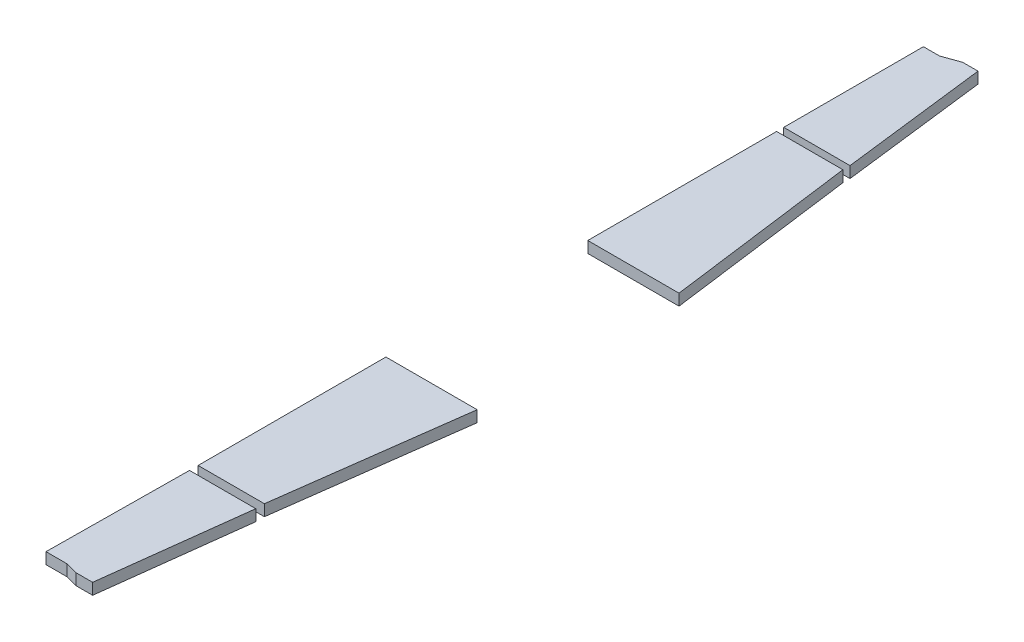
SolidWorks part; units mm, degrees
ref_plane "Front Plane" through (0, 0, 0) normal (0, 0, 1) x (1, 0, 0)
ref_plane "Top Plane" through (0, 0, 0) normal (0, 1, 0) x (1, 0, 0)
ref_plane "Right Plane" through (0, 0, 0) normal (1, 0, 0) x (0, 0, -1)
sketch "Sketch1" plane through (0, 0, 0) normal (0, 1, 0) x (1, 0, 0)
  line L0 (0, 0) -> (1188.6667, 0) construction
  line L1 (1886.6416, -10754.9704) -> (4446.1038, -10754.9704)
  line L2 (4446.1038, -10754.9704) -> (3757.6552, -6813.8602)
  line L3 (3757.6552, -6813.8602) -> (3166.3727, -6813.8602)
  line L4 (3166.3727, -6813.8602) -> (2506.2895, -6979.2389)
  line L5 (2506.2895, -6979.2389) -> (1886.6416, -6979.2389)
  line L6 (1886.6416, -6979.2389) -> (1886.6416, -10754.9704)
  line L7 (1886.6416, -10947.5155) -> (4446.1038, -10947.5155)
  line L8 (1886.6416, -10947.5155) -> (1886.6416, -16051.7647)
  line L9 (1886.6416, -16051.7647) -> (5410.4156, -16051.7647)
  line L10 (5410.4156, -16051.7647) -> (4446.1038, -10947.5155)
  line L11 (1886.6416, -21507.5385) -> (1886.6416, -26583.6069)
  line L12 (1886.6416, -21507.5385) -> (5410.4156, -21507.5385)
  line L13 (5410.4156, -21507.5385) -> (4446.1038, -26583.6069)
  line L14 (4446.1038, -26583.6069) -> (2301.3562, -26583.6069)
  line L15 (2301.3562, -26583.6069) -> (1886.6416, -26583.6069)
  line L16 (1886.6416, -26816.2701) -> (1832.6361, -30657.2626)
  line L17 (1832.6361, -30657.2626) -> (2648.847, -30657.2626)
  line L18 (2648.847, -30657.2626) -> (3108.5383, -30744.5911)
  line L19 (3108.5383, -30744.5911) -> (3757.6552, -30744.5911)
  line L20 (3757.6552, -30744.5911) -> (4446.1038, -26816.2701)
  line L21 (4446.1038, -26816.2701) -> (1886.6416, -26816.2701)
extrude "Boss-Extrude1" add sketch "Sketch1" along normal blind 304.8
sketch "Sketch4" plane through (0, 0, 30744.5911) normal (0, 0, 1) x (1, 0, 0)
  line L12 (1832.6361, 304.8) -> (1832.6361, 0) construction
  line L15 (1832.6361, 304.8) -> (2648.847, 304.8) construction
  circle A0 centre (1959.6361, 152.4) radius 76.2
  dimension "D2" = 152.4
  dimension "D1" = 127
  dimension "D3" = 76.2
sketch "Sketch7" plane through (0, 0, 21507.5385) normal (0, 0, -1) x (-1, 0, 0)
  line L4 (-1886.6416, 304.8) -> (-1886.6416, 0) construction
  line L7 (-5410.4156, 304.8) -> (-1886.6416, 304.8) construction
  circle A0 centre (-2089.8416, 152.4) radius 76.2
  dimension "D1" = 127
  dimension "D2" = 76.2
sketch "Sketch10" plane through (0, 0, 16051.7647) normal (0, 0, 1) x (1, 0, 0)
  line L8 (1886.6416, 304.8) -> (1886.6416, 0) construction
  line L9 (1886.6416, 304.8) -> (5410.4156, 304.8) construction
  circle A0 centre (2013.6416, 152.4) radius 76.2
  dimension "D2" = 152.4
  dimension "D1" = 127
sketch "Sketch11" plane through (0, 0, 6813.8602) normal (0, 0, -1) x (-1, 0, 0)
  line L9 (-1886.6416, 304.8) -> (-1886.6416, 0) construction
  line L10 (-2506.2895, 304.8) -> (-1886.6416, 304.8) construction
  circle A0 centre (-2025.8742, 152.4) radius 101.6
  dimension "D1" = 139.2326
  dimension "D2" = 152.4
scale "Scale5" bodies to scale 103 104 101 102 scale about origin uniform scaling no x scale factor 0.7 y scale factor 1 z scale factor 1
